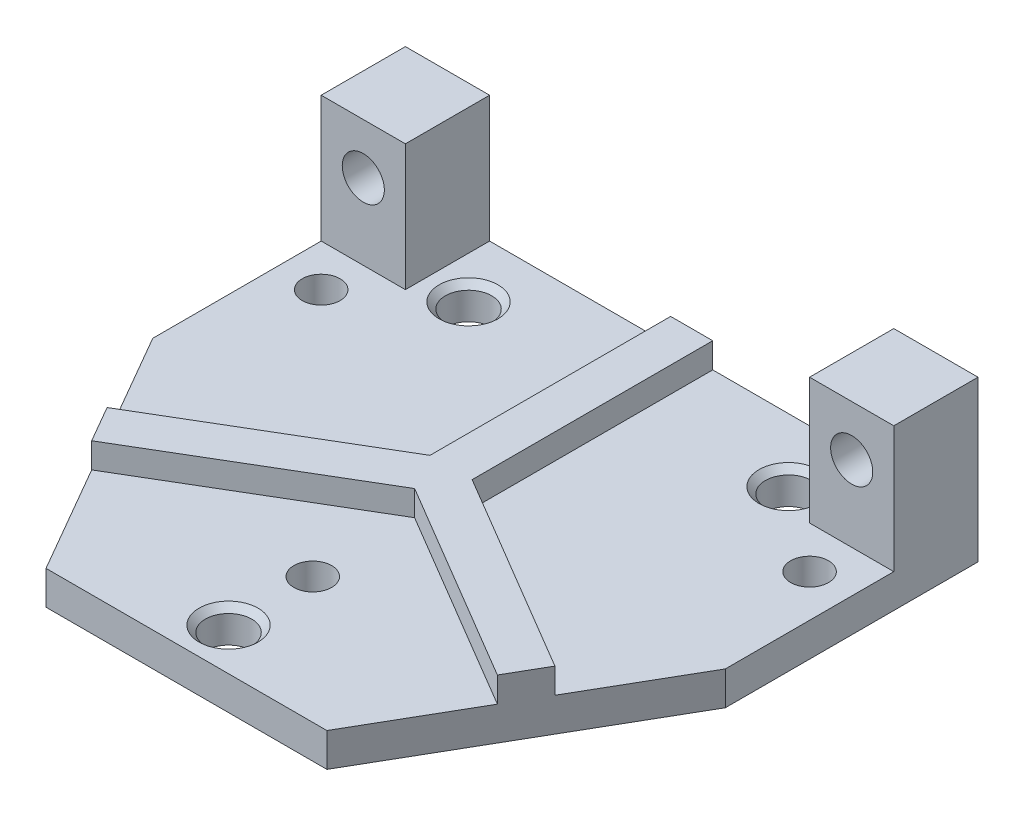
SolidWorks part; units mm, degrees
material "PET"
ref_plane "Front Plane" through (0, 0, 0) normal (0, 0, 1) x (1, 0, 0)
ref_plane "Top Plane" through (0, 0, 0) normal (0, 1, 0) x (1, 0, 0)
ref_plane "Right Plane" through (0, 0, 0) normal (1, 0, 0) x (0, 0, -1)
sketch "Sketch1" plane through (0, 0, 0) normal (0, 1, 0) x (1, 0, 0)
  line L0 (-30, 15) -> (30, 15) construction
  line L1 (-16.6795, -30) -> (16.6795, -30)
  line L2 (-34, 0) -> (-34, 30)
  line L3 (-34, 30) -> (34, 30)
  line L4 (34, 0) -> (34, 30)
  line L5 (-22.5251, -19.8751) -> (34, 30) construction
  line L6 (-34, 30) -> (22.5251, -19.8751) construction
  line L7 (-34, 22.5) -> (34, 22.5) construction
  line L8 (-34, -25) -> (34, -25) construction
  line L9 (-34, 0) -> (-16.6795, -30)
  line L10 (16.6795, -30) -> (34, 0)
  line L11 (0, -30) -> (0, -15) construction
  line L12 (0, -25) -> (0, -15) construction
  line L13 (-34, 0) -> (34, 0) construction
  circle A0 centre (-19, 22.5) radius 2.75
  circle A1 centre (19, 22.5) radius 2.75
  circle A2 centre (0, -25) radius 2.75
  circle A3 centre (-29, 15) radius 2.25
  circle A4 centre (29, 15) radius 2.25
  circle A5 centre (0, -15) radius 2.25
  point P0 (0, 0)
  dimension "D5" = 5.5
  dimension "D6" = 5.5
  dimension "D7" = 5.5
  dimension "D8" = 4.5
  dimension "D9" = 4.5
  dimension "D10" = 5
  dimension "D11" = 5
  dimension "D13" = 4.5
  dimension "D14" = 15
  dimension "D21" = 15
  dimension "D2" = 68
  dimension "D3" = 47.5
  dimension "D4" = 7.5
  dimension "D12" = 15
  dimension "D15" = 120
  dimension "D16" = 120
  dimension "D17" = 30
  dimension "D18" = 34
  dimension "D19" = 60
  dimension "D20" = 15
extrude "Boss-Extrude1" add sketch "Sketch1" along normal blind 4
sketch "Sketch2" plane through (0, 4, 0) normal (0, 1, 0) x (1, 0, 0)
  line L0 (-25.3397, -15) -> (0, 0) construction
  line L1 (-34, 0) -> (-16.6795, -30) construction
  line L2 (0, 0) -> (0, 30) construction
  line L3 (34, 30) -> (-34, 30) construction
  line L4 (0, 0) -> (25.3397, -15) construction
  line L5 (16.6795, -30) -> (34, 0) construction
  line L6 (-24.0663, -17.1513) -> (0, -2.9052) construction
  line L7 (-26.6132, -12.8487) -> (-2.5, 1.4253) construction
  line L8 (-26.5898, -12.8348) -> (-24.0897, -17.1652)
  line L9 (0, -2.9052) -> (24.0663, -17.1513) construction
  line L10 (2.5, 1.4253) -> (26.6132, -12.8487) construction
  line L11 (24.0897, -17.1652) -> (26.5898, -12.8348)
  line L12 (-26.5898, -12.8348) -> (-2.5, 1.4253)
  line L13 (-2.5, 1.4253) -> (-2.5, 30)
  line L14 (2.5, 1.4253) -> (26.5898, -12.8348)
  line L15 (2.5, 1.4253) -> (2.5, 30)
  line L16 (-24.0897, -17.1652) -> (0, -2.9052)
  line L17 (0, -2.9052) -> (24.0897, -17.1652)
  line L18 (-2.5, 30) -> (2.5, 30)
  dimension "D1" = 2.5
  dimension "D2" = 2.5
  dimension "D3" = 2.5
extrude "Boss-Extrude2" add sketch "Sketch2" along normal blind 3
sketch "Sketch3" plane through (0, 4, 0) normal (0, 1, 0) x (1, 0, 0)
  line L1 (-34, 30) -> (-24, 30)
  line L2 (-34, 30) -> (-34, 20)
  line L3 (-34, 20) -> (-24, 20)
  line L4 (-24, 30) -> (-24, 20)
  line L5 (34, 30) -> (24, 30)
  line L6 (34, 30) -> (34, 20)
  line L7 (34, 20) -> (24, 20)
  line L8 (24, 30) -> (24, 20)
  dimension "D1" = 10
  dimension "D2" = 10
  dimension "D3" = 10
extrude "Boss-Extrude3" add sketch "Sketch3" along normal blind 15
sketch "Sketch4" plane through (0, 0, -30) normal (0, 0, -1) x (-1, 0, 0)
  line L0 (-24, 19) -> (-34, 7) construction
  line L1 (24, 19) -> (34, 19) construction
  line L2 (24, 19) -> (34, 7) construction
  line L4 (-34, 19) -> (-24, 19) construction
  line L5 (-34, 19) -> (-34, 0) construction
  line L6 (34, 19) -> (34, 0) construction
  circle A0 centre (-29, 13) radius 2.5
  circle A1 centre (29, 13) radius 2.5
  dimension "D3" = 5
  dimension "D4" = 5
  dimension "D5" = 6
  dimension "D1" = 6
extrude "Cut-Extrude1" cut sketch "Sketch4" against normal through all
chamfer "Chamfer1" distance 0.75 angle 45 3 edges at (0, 4, 27.75) (-19, 4, -19.75) (19, 4, -19.75)
